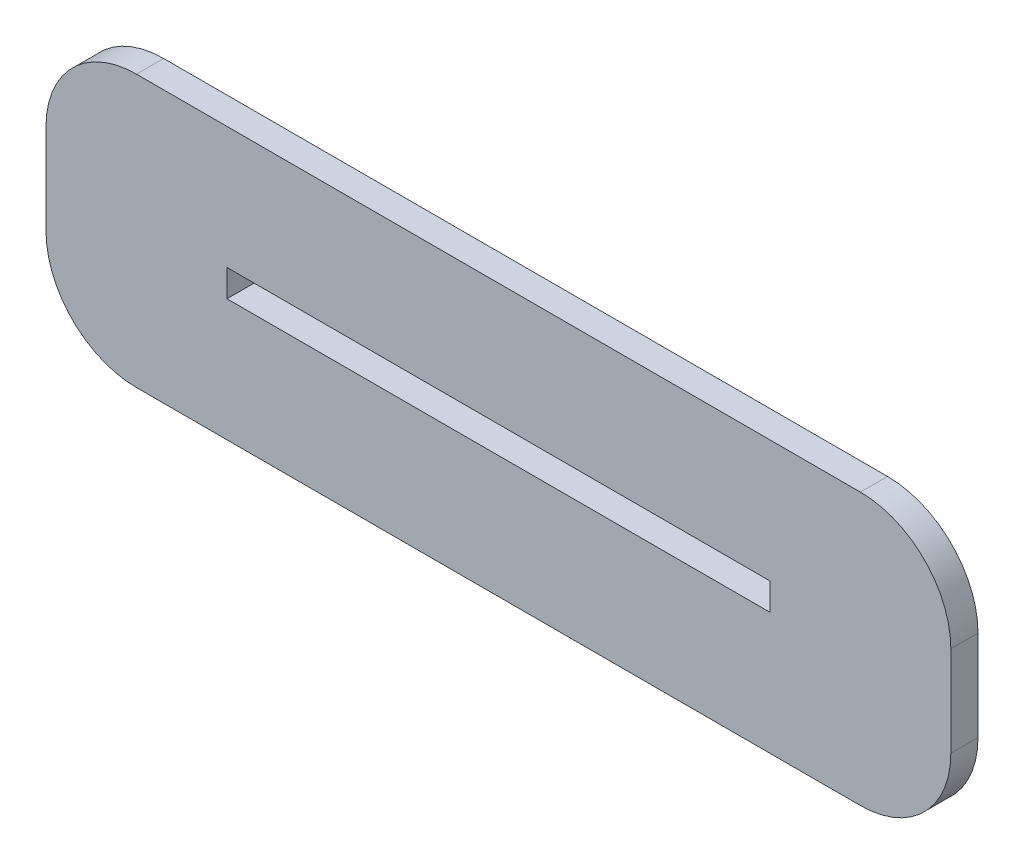
SolidWorks part; units mm, degrees
ref_plane "Front Plane" through (0, 0, 0) normal (0, 0, 1) x (1, 0, 0)
ref_plane "Top Plane" through (0, 0, 0) normal (0, 1, 0) x (1, 0, 0)
ref_plane "Right Plane" through (0, 0, 0) normal (1, 0, 0) x (0, 0, -1)
sketch "Sketch1" plane through (0, 0, 0) normal (0, 0, 1) x (1, 0, 0)
  line L0 (0, 15) -> (165.98, 15) construction
  line L1 (0, 0) -> (100, 0)
  line L2 (0, 0) -> (0, 30)
  line L3 (0, 30) -> (100, 30)
  line L4 (100, 0) -> (100, 30)
  line L6 (20, 13.5) -> (80, 13.5)
  line L7 (20, 13.5) -> (20, 16.5)
  line L8 (20, 16.5) -> (80, 16.5)
  line L9 (80, 13.5) -> (80, 16.5)
  line L10 (20, 13.5) -> (80, 16.5) construction
  line L11 (20, 16.5) -> (80, 13.5) construction
  point P7 (50, 15)
  dimension "D1" = 30
  dimension "D2" = 100
  dimension "D3" = 60
  dimension "D4" = 3
  dimension "D5" = 20
extrude "Boss-Extrude1" add sketch "Sketch1" along normal blind 3
fillet "Fillet1" radius 10 4 edges at (0, 30, 1.5) (0, 0, 1.5) (100, 0, 1.5) (100, 30, 1.5)
